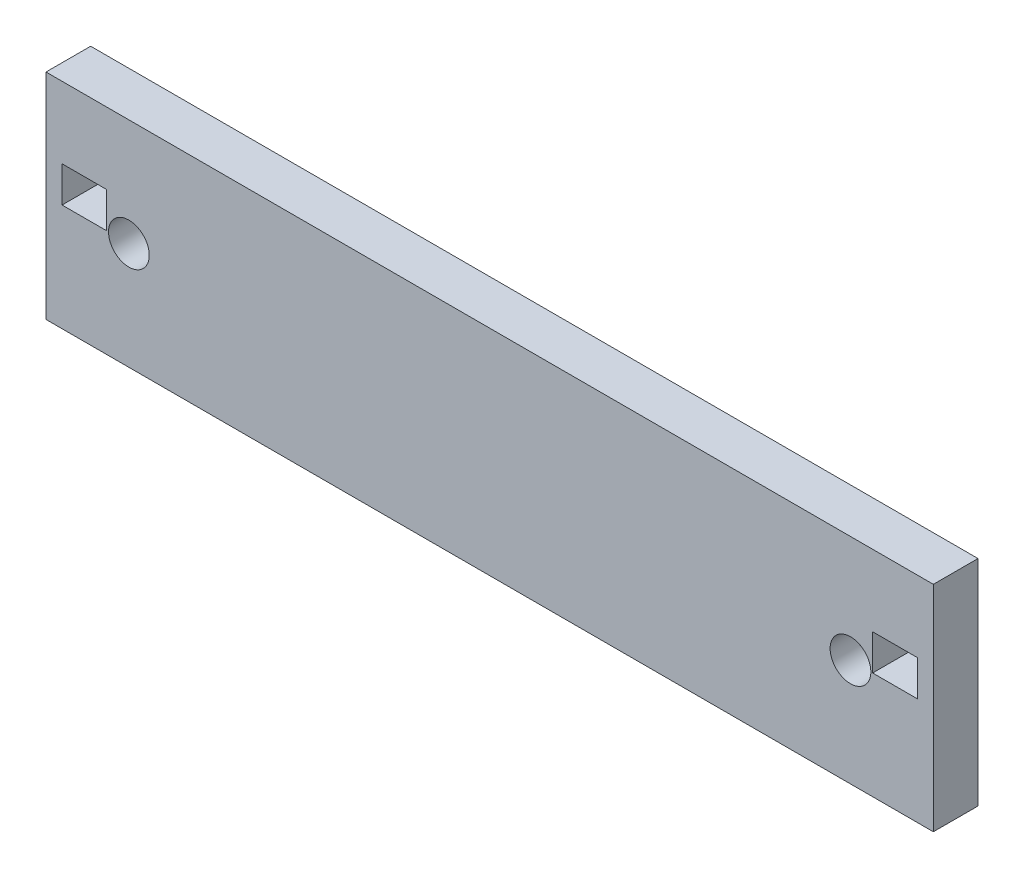
SolidWorks part; units mm, degrees
material "Beech"
ref_plane "Front Plane" through (0, 0, 0) normal (0, 0, 1) x (1, 0, 0)
ref_plane "Top Plane" through (0, 0, 0) normal (0, 1, 0) x (1, 0, 0)
ref_plane "Right Plane" through (0, 0, 0) normal (1, 0, 0) x (0, 0, -1)
sketch "Sketch1" plane through (0, 0, 0) normal (0, 0, 1) x (1, 0, 0)
  line L0 (0, -1000) -> (0, 49000) construction
  line L1 (-18.034, -3.81) -> (13.5128, -3.81)
  line L2 (-18.034, -3.81) -> (-18.034, 3.81)
  line L3 (-18.034, 3.81) -> (13.5128, 3.81)
  line L4 (13.5128, -3.81) -> (13.5128, 3.81)
  line L5 (12.9413, 1.27) -> (13.5128, 1.27) construction
  line L6 (10.5664, -3.81) -> (10.5664, 0) construction
  line L7 (-17.4625, 0) -> (-15.875, 0)
  line L8 (-17.4625, 0) -> (-17.4625, 1.27)
  line L9 (-17.4625, 1.27) -> (-15.875, 1.27)
  line L10 (-15.875, 0) -> (-15.875, 1.27)
  line L11 (11.3538, 0) -> (11.3538, 1.27)
  line L12 (12.9413, 1.27) -> (11.3538, 1.27)
  line L13 (12.9413, 0) -> (12.9413, 1.27)
  line L14 (12.9413, 0) -> (11.3538, 0)
  line L15 (-1000, 0) -> (49000, 0) construction
  line L16 (10.5664, 0) -> (10.5664, 3.81) construction
  line L17 (-17.4625, 1.27) -> (-18.034, 1.27) construction
  circle A0 centre (-15.0876, 0) radius 0.7239
  circle A1 centre (10.5664, 0) radius 0.7239
  point P0 (0, 0)
  dimension "D6" = 1.4478
  dimension "D7" = 0.7874
  dimension "D1" = 0.5715
  dimension "D2" = 7.62
  dimension "D3" = 1.5875
  dimension "D4" = 15.875
  dimension "D5" = 1.27
  dimension "D8" = 0.7874
  dimension "D9" = 25.654
extrude "Boss-Extrude1" add sketch "Sketch1" along normal blind 1.5875
move or copy body "Body-Move/Copy1" [suppressed] bodies to move or copy 101
